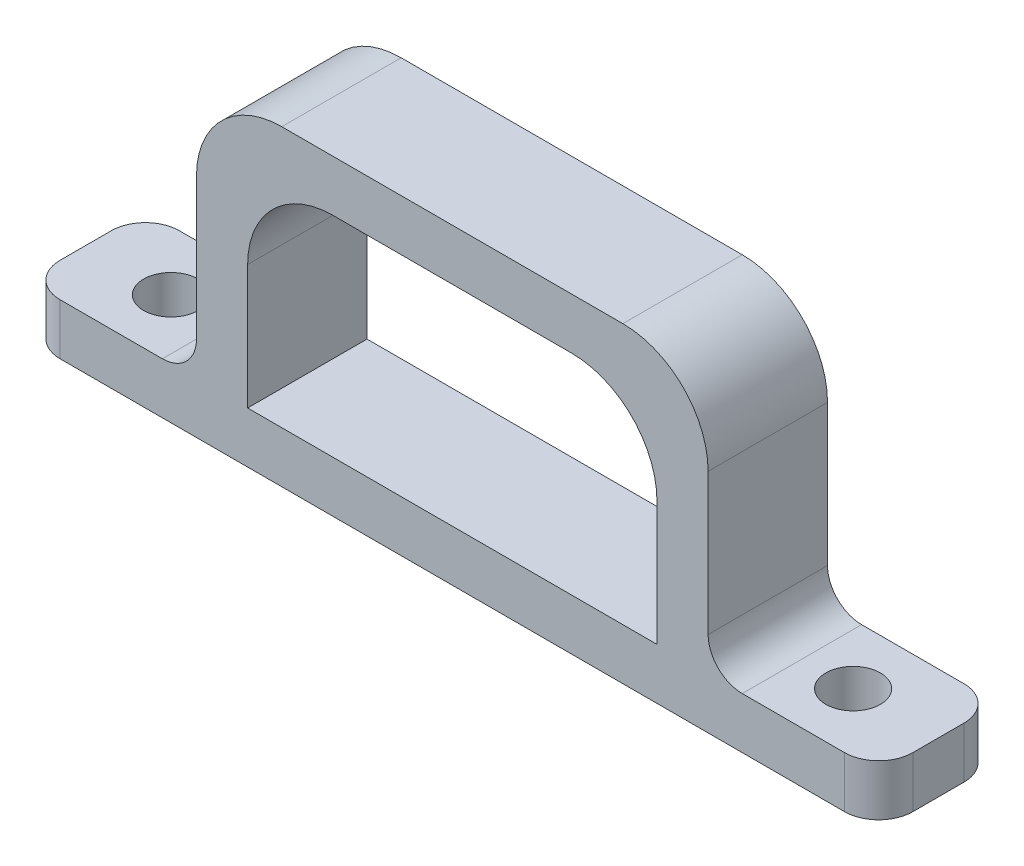
SolidWorks part; units mm, degrees
ref_plane "Front Plane" through (0, 0, 0) normal (0, 0, 1) x (1, 0, 0)
ref_plane "Top Plane" through (0, 0, 0) normal (0, 1, 0) x (1, 0, 0)
ref_plane "Right Plane" through (0, 0, 0) normal (1, 0, 0) x (0, 0, -1)
sketch "Sketch2" plane through (0, 0, 0) normal (0, 0, 1) x (1, 0, 0)
  line L1 (-25, -1.5) -> (25, -1.5)
  line L2 (-25, -1.5) -> (-25, 1.5)
  line L3 (-25, 1.5) -> (25, 1.5)
  line L4 (25, -1.5) -> (25, 1.5)
  line L5 (-25, -1.5) -> (25, 1.5) construction
  line L6 (-25, 1.5) -> (25, -1.5) construction
  line L7 (-15, 1.5) -> (15, 1.5)
  line L8 (-15, 1.5) -> (-15, 16.7836)
  line L9 (-15, 16.7836) -> (15, 16.7836)
  line L10 (15, 1.5) -> (15, 16.7836)
  line L11 (-12, 1.5) -> (12, 1.5)
  line L12 (-12, 1.5) -> (-12, 13.7836)
  line L13 (-12, 13.7836) -> (12, 13.7836)
  line L14 (12, 1.5) -> (12, 13.7836)
  point P0 (0, 0)
  dimension "D1" = 50
  dimension "D2" = 3
  dimension "D3" = 10
  dimension "D4" = 3
  dimension "D5" = 3
  dimension "D6" = 3
  dimension "D7" = 10
extrude "Boss-Extrude1" add sketch "Sketch2" along normal blind 7 contours L1 L4 L3 L7 L2 | L14 L3 L10 L9 L8 L12 L13
sketch "Sketch3" plane through (0, 1.5, 0) normal (0, 1, 0) x (1, 0, 0)
  line L1 (-25, -7) -> (-25, 0) construction
  line L2 (-25, -7) -> (-15, -7) construction
  line L3 (15, 0) -> (25, 0) construction
  circle A0 centre (-20, -3.5) radius 1.6
  circle A1 centre (20, -3.5) radius 1.6
  dimension "D1" = 3.2
  dimension "D2" = 3.2
  dimension "D3" = 40
  dimension "D4" = 5
  dimension "D5" = 3.5
  dimension "D6" = 3.5
extrude "Cut-Extrude1" cut sketch "Sketch3" against normal blind 7
fillet "Fillet1" radius 5 4 edges at (-12, 13.7836, 3.5) (12, 13.7836, 3.5) (15, 16.7836, 3.5) (-15, 16.7836, 3.5)
fillet "Fillet2" radius 2 6 edges at (25, 0, 0) (25, 0, 7) (15, 1.5, 3.5) (-15, 1.5, 3.5) (-25, 0, 0) (-25, 0, 7)
